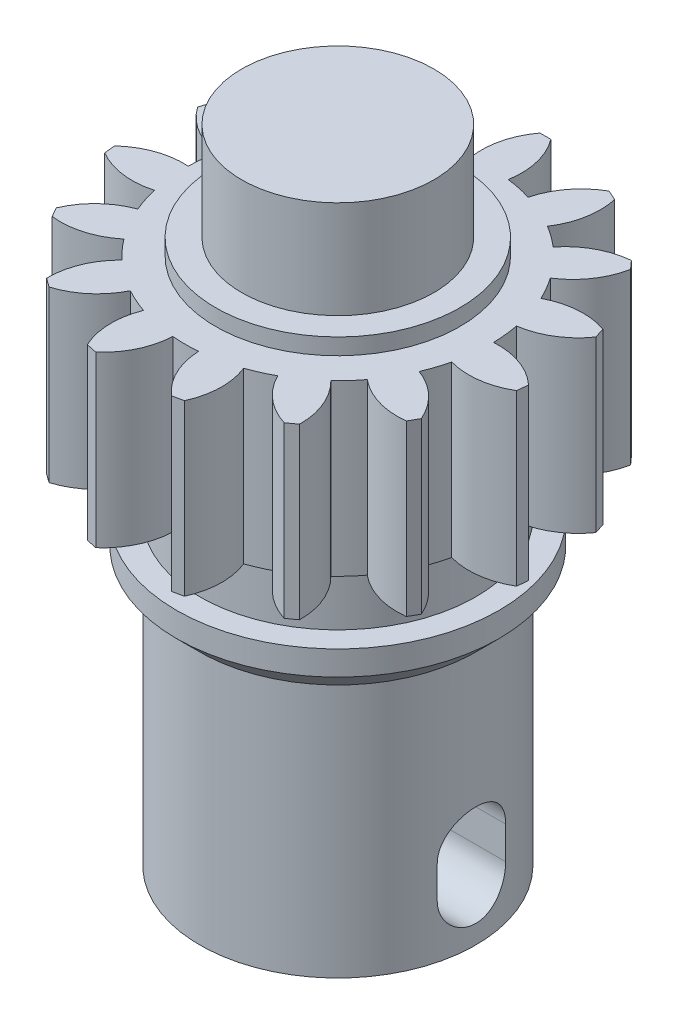
SolidWorks part; units mm, degrees
ref_plane "Plano frontal" through (0, 0, 0) normal (0, 0, 1) x (1, 0, 0)
ref_plane "Plano superior" through (0, 0, 0) normal (0, 1, 0) x (1, 0, 0)
ref_plane "Plano direito" through (0, 0, 0) normal (1, 0, 0) x (0, 0, -1)
sketch "Esboço1" plane through (0, 0, 0) normal (0, 0, 1) x (1, 0, 0)
  line L0 (0, 0) -> (0, 39.4)
  line L1 (0, 0) -> (8.47, 0)
  line L2 (8.47, 0) -> (8.47, 15.58)
  line L3 (8.47, 15.58) -> (9.9, 17.01)
  line L4 (9.9, 17.01) -> (9.9, 18.51)
  line L5 (9.9, 18.51) -> (8.47, 18.51)
  line L6 (8.47, 18.51) -> (8.47, 22)
  line L7 (8.47, 22) -> (9.374, 22)
  line L8 (9.374, 22) -> (9.374, 32.4)
  line L9 (9.374, 32.4) -> (7.5, 32.4)
  line L10 (7.5, 32.4) -> (7.5, 33.4)
  line L11 (7.5, 33.4) -> (5.9, 33.4)
  line L12 (5.9, 33.4) -> (5.9, 39.4)
  line L13 (5.9, 39.4) -> (0, 39.4)
  dimension "D1" = 8.47
  dimension "D2" = 22
  dimension "D3" = 3.49
  dimension "D4" = 1.5
  dimension "D5" = 135
  dimension "D6" = 9.9
  dimension "D7" = 9.374
  dimension "D8" = 7.5
  dimension "D9" = 10.4
  dimension "D10" = 1
  dimension "D11" = 6
  dimension "D12" = 5.9
revolve "Revolução1" add sketch "Esboço1" angle 360 about L0
sketch "Esboço2" plane through (0, 32.4, 0) normal (0, 1, 0) x (1, 0, 0)
  line L0 (-0.337, 12.746) -> (0.337, 12.746)
  line L1 (0, 0) -> (0, 0.674) construction
  line L2 (0, 0) -> (0, 12.746) construction
  line L3 (0, 0) -> (3.269, 10.0539) construction
  arc A1 (1.1676, 9.301) -> (-1.1676, 9.301) centre (0, 0) ccw
  arc A3 (0.337, 12.746) -> (1.1676, 9.301) centre (-3.269, 10.0539) cw
  arc A4 (-0.337, 12.746) -> (-1.1676, 9.301) centre (3.269, 10.0539) ccw
  point P3 (0, 12.746)
  dimension "D2" = 12.746
  dimension "D3" = 18.012
  dimension "D5" = 18.748
  dimension "D1" = 0.674
  dimension "D4" = 10.572
extrude "Ressalto-extrusão1" add sketch "Esboço2" against normal up to surface (10.4 mm away) up to face at (0, 22, -9.374)
pattern_circular "PadrãoCircular1" count 15 over 360 about axis through (0, 0, 0) along (0, 1, 0) of "Ressalto-extrusão1"
sketch "Esboço3" plane through (0, 0, 0) normal (0, -1, 0) x (1, 0, 0)
  line L0 (-3.25, 4.7183) -> (-3.25, -5.2191) construction
  line L1 (2.75, 1.7321) -> (2.75, -1.7321)
  arc A0 (2.75, 1.7321) -> (2.75, -1.7321) centre (0, 0) ccw
  dimension "D1" = 6.5
  dimension "D2" = 6
extrude "Corte-extrusão1" cut sketch "Esboço3" against normal blind 22
sketch "Esboço4" plane through (0, 0, 0) normal (0, -1, 0) x (1, 0, 0)
  circle A0 centre (0, 0) radius 3.25
  dimension "D1" = 6.5
extrude "Corte-extrusão2" cut sketch "Esboço4" against normal blind 4
sketch "Esboço7" plane through (0, 0, 0) normal (1, 0, 0) x (0, 0, -1)
  line L0 (-2.1, 5.25) -> (2.1, 5.25) construction
  line L2 (-2.1, 5.25) -> (-2.1, 3.25)
  line L4 (2.1, 5.25) -> (2.1, 3.25)
  arc A0 (-2.1, 5.25) -> (2.1, 5.25) centre (0, 5.25) cw
  arc A1 (-2.1, 3.25) -> (2.1, 3.25) centre (0, 3.25) ccw
  dimension "D3" = 2.1
  dimension "D2" = 2
  dimension "D4" = 3.25
extrude "Corte-extrusão4" cut sketch "Esboço7" against normal mid plane 40
